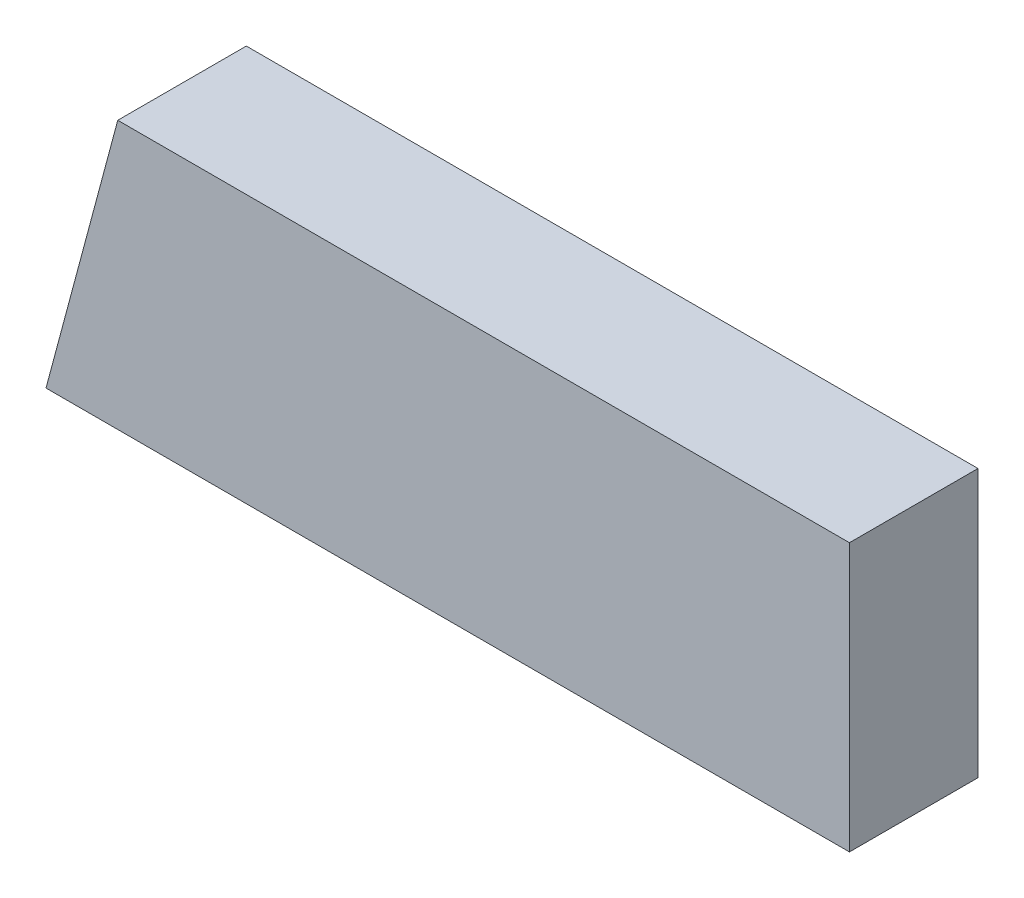
SolidWorks part; units mm, degrees
ref_plane "Front Plane" through (0, 0, 0) normal (0, 0, 1) x (1, 0, 0)
ref_plane "Top Plane" through (0, 0, 0) normal (0, 1, 0) x (1, 0, 0)
ref_plane "Right Plane" through (0, 0, 0) normal (1, 0, 0) x (0, 0, -1)
sketch "Sketch1" plane through (0, 0, 0) normal (0, 0, 1) x (0.9659, -0.2588, 0)
  line L0 (-36.3041, 4.2763) -> (29.6699, 21.9539)
  line L1 (36.1404, -2.1942) -> (-36.3041, -21.6056)
  line L2 (-36.3041, -21.6056) -> (-36.3041, 4.2763)
  line L3 (36.1404, -2.1942) -> (29.6699, 21.9539)
  dimension "D1" = 25
  dimension "D2" = 75
  dimension "D3" = 75
extrude "Boss-Extrude1" add sketch "Sketch1" against normal blind 12 contours L0 L3 L1 L2
